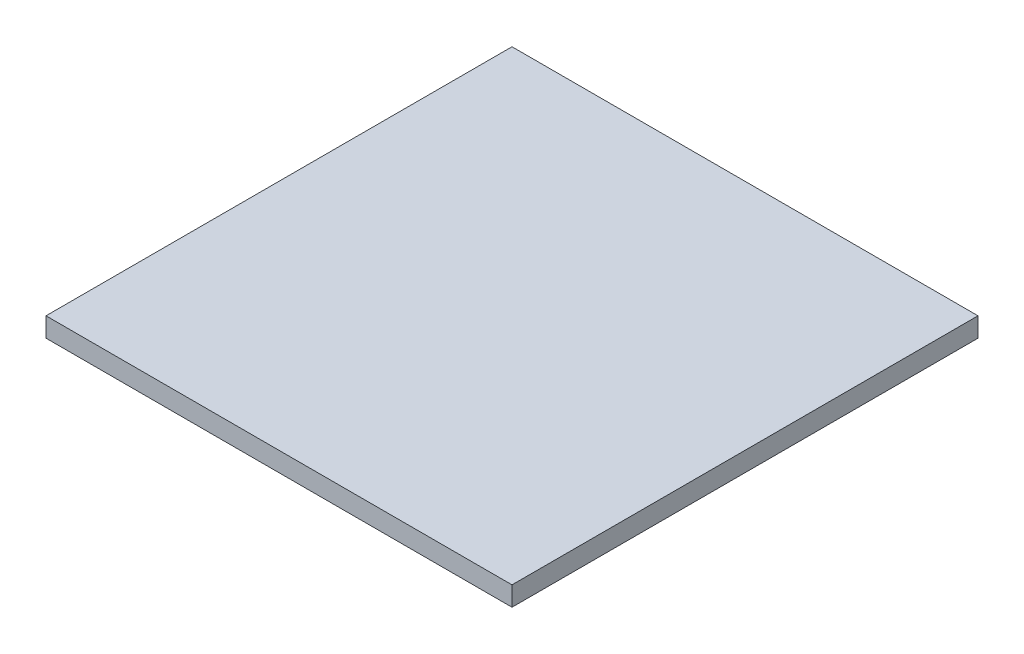
SolidWorks part; units mm, degrees
ref_plane "Front Plane" through (0, 0, 0) normal (0, 0, 1) x (1, 0, 0)
ref_plane "Top Plane" through (0, 0, 0) normal (0, 1, 0) x (1, 0, 0)
ref_plane "Right Plane" through (0, 0, 0) normal (1, 0, 0) x (0, 0, -1)
sketch "Szkic1" plane through (0, 0, 0) normal (0, 1, 0) x (1, 0, 0)
  line L1 (6, -6) -> (-6, -6)
  line L2 (6, -6) -> (6, 6)
  line L3 (6, 6) -> (-6, 6)
  line L4 (-6, -6) -> (-6, 6)
  line L5 (6, -6) -> (-6, 6) construction
  line L6 (6, 6) -> (-6, -6) construction
  point P0 (0, 0)
  dimension "D1" = 12
extrude "Dodanie-wyciągnięcie1" add sketch "Szkic1" along normal blind 0.5
